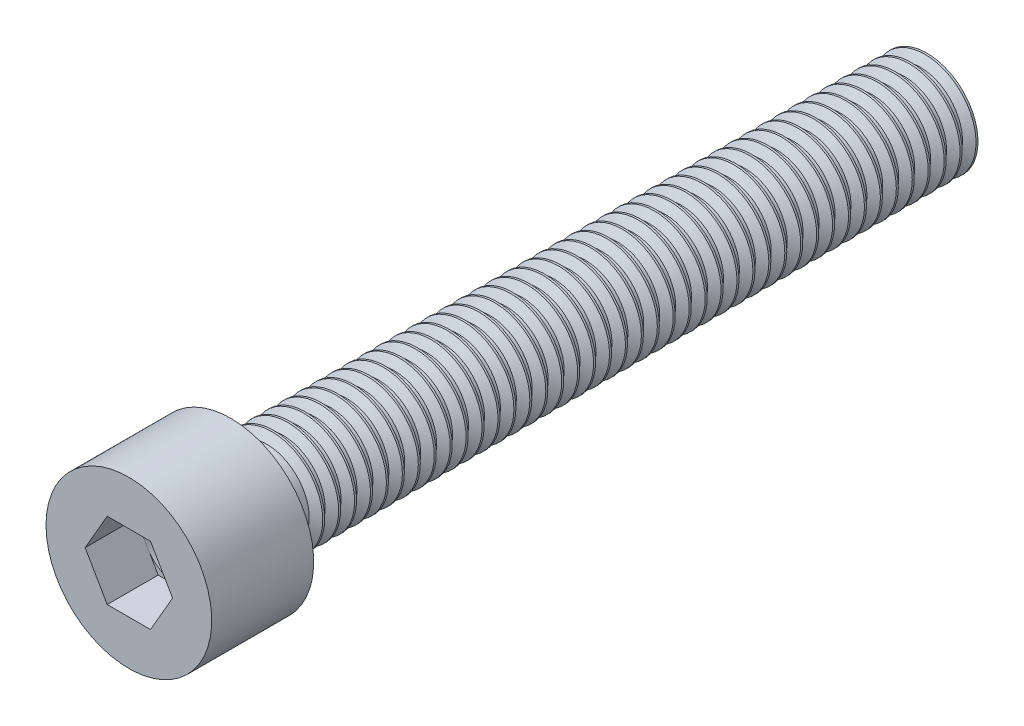
SolidWorks part; units mm, degrees
ref_plane "Plane1" through (0, 0, 0) normal (0, 0, 1) x (1, 0, 0)
ref_plane "Plane2" through (0, 0, 0) normal (0, 1, 0) x (1, 0, 0)
ref_plane "Plane3" through (0, 0, 0) normal (1, 0, 0) x (0, 0, -1)
sketch "Sketch1" plane through (0, 0, 0) normal (0, 0, 1) x (1, 0, 0)
  circle A0 centre (0, 0) radius 3.3281
  dimension "D1" = 6.6563
extrude "Base-Extrude" add sketch "Sketch1" along normal blind 55
sketch "Sketch2" plane through (0, 0, 0) normal (0, 1, 0) x (1, 0, 0)
  line L0 (3.3281, 0) -> (4, -0.3879)
  line L1 (3.3281, 0) -> (-3.3281, 0) construction
  line L2 (4, -0.3879) -> (4, -0.5442)
  line L4 (4, -0.5442) -> (3.3281, -0.9321)
  line L5 (3.3281, -55) -> (3.3281, 0) construction
  line L6 (3.3281, 0) -> (3.3281, -0.9321)
  dimension "D1" = 60
  dimension "D2" = 4
  dimension "D3" = 0.1562
  dimension "D4" = 3.3281
  dimension "D9" = 60
ref_plane "Plane5" through (0, 0, 0.5) normal (0, 0, -1) x (-1, 0, 0)
sketch "Sketch4" plane through (0, 0, 0.5) normal (0, 0, -1) x (-1, 0, 0)
  circle A0 centre (0, 0) radius 3.3281 construction
  circle A1 centre (0, 0) radius 3.3281
sweep "Boss-Sweep1" add profiles "Sketch2" path "Sketch4"
sketch "Sketch5" plane through (0, 0, 0) normal (0, 1, 0) x (1, 0, 0)
  line L0 (0, 0) -> (0, -1.4038)
  line L2 (0, -0.3879) -> (0, 0) construction
pattern_linear "LPattern1" count 42 spacing 1.25 along (0, 0, 1) of "Boss-Sweep1"
sketch "Sketch7" plane through (0, 0, 0) normal (0, 1, 0) x (1, 0, 0)
  line L0 (0, 0) -> (0, -22.3053) construction
  line L1 (0, -15) -> (0, -14.6821) construction
  line L2 (0, -55) -> (6.5, -55)
  line L3 (6.5, -55) -> (6.5, -63)
  line L5 (6.5, -63) -> (0, -63)
  line L6 (0, -63) -> (0, -55)
  dimension "D13" = 8
  dimension "D12" = 6.5
  dimension "D14" = 55
revolve "Boss-Revolve2" add sketch "Sketch7" angle 360 about L0
sketch "Sketch8" plane through (0, 0, 63) normal (0, 0, 1) x (1, 0, 0)
  line L0 (-5, 0) -> (5, 0) construction
  line L1 (0, 6.1) -> (0, -5.8) construction
  line L4 (-1.6979, 3) -> (1.6979, 3)
  line L5 (1.6979, 3) -> (3.43, 0)
  line L6 (-1.6979, 3) -> (-3.43, 0)
  line L7 (1.6979, -3) -> (3.43, 0)
  line L8 (-1.6979, -3) -> (1.6979, -3)
  line L9 (-1.6979, -3) -> (-3.43, 0)
  dimension "D1" = 3.43
  dimension "D2" = 60
  dimension "D16" = 6.86
  dimension "D15" = 6
extrude "Cut-Extrude2" cut sketch "Sketch8" against normal blind 4
sketch "Sketch9" plane through (0, 0, 0) normal (0, 1, 0) x (1, 0, 0)
  line L0 (0, 0) -> (0, -35.025) construction
  line L1 (0, -0.5442) -> (0, -0.9321) construction
  line L2 (0, -59) -> (3, -59)
  line L3 (3, -59) -> (3, -58.2)
  line L4 (3, -58.2) -> (0, -57.3962)
  line L5 (0, -57.3962) -> (0, -59)
  dimension "D1" = 15
  dimension "D18" = 3
  dimension "D19" = 0.8
  dimension "D20" = 59
revolve "Cut-Revolve1" cut sketch "Sketch9" angle 360 about L0
